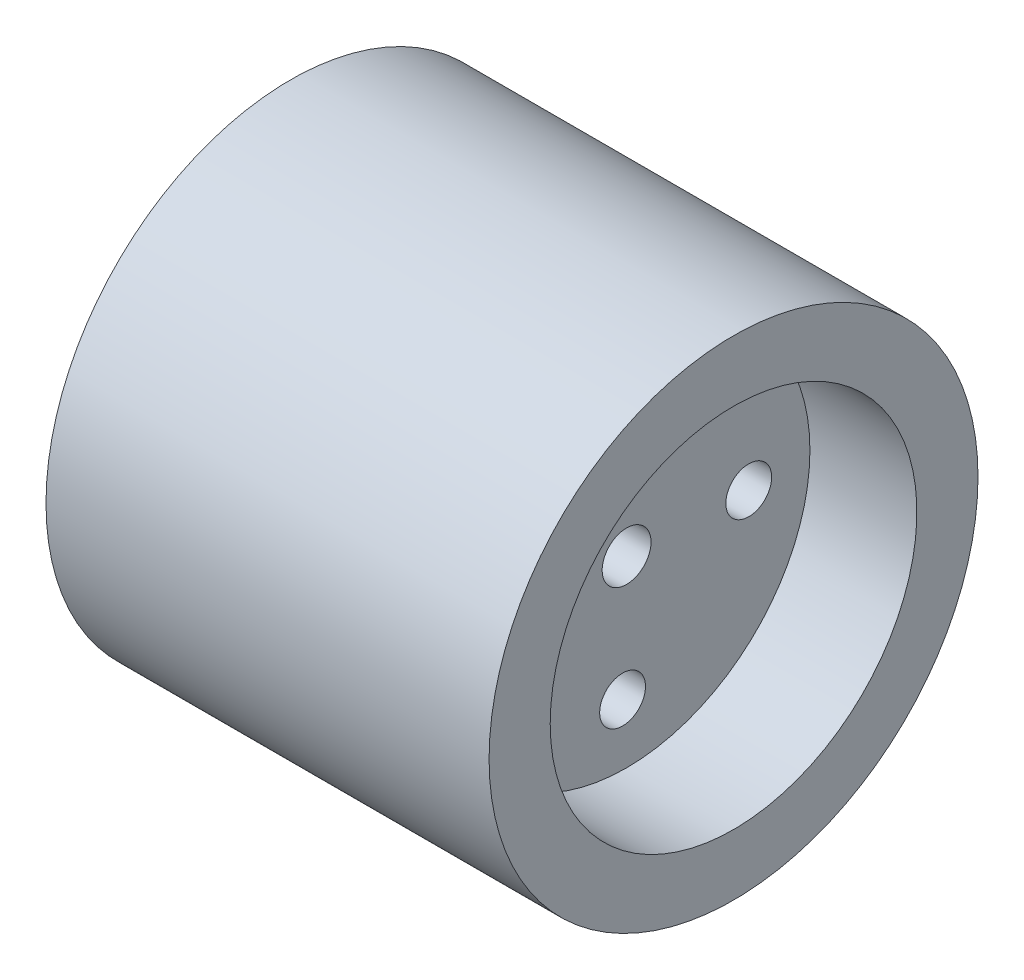
SolidWorks part; units mm, degrees
material "ABS"
ref_plane "Front Plane" through (0, 0, 0) normal (0, 0, 1) x (1, 0, 0)
ref_plane "Top Plane" through (0, 0, 0) normal (0, 1, 0) x (1, 0, 0)
ref_plane "Right Plane" through (0, 0, 0) normal (1, 0, 0) x (0, 0, -1)
sketch "Sketch3" plane through (0, 0, 0) normal (0, 0, 1) x (1, 0, 0)
  line L0 (0, 0) -> (18, 0) construction
  line L1 (-7, 1.6) -> (6, 1.6)
  line L2 (6, 1.6) -> (6, 12)
  line L6 (15, 12) -> (15, 16)
  line L7 (15, 16) -> (-14, 16)
  line L9 (-16, 13) -> (-7, 13)
  line L10 (-7, 13) -> (-7, 1.6)
  line L11 (15, 12) -> (6, 12)
  line L12 (-16, 18) -> (-16, 13)
  line L15 (-16, 18) -> (-14, 18)
  line L16 (-14, 16) -> (-14, 18)
  dimension "D1" = 3.2
  dimension "D2" = 9
  dimension "D3" = 32
  dimension "D4" = 31
  dimension "D5" = 13
  dimension "D6" = 18
  dimension "D7" = 24
  dimension "D8" = 3
  dimension "D9" = 3
  dimension "D10" = 2
  dimension "D11" = 2
revolve "Revolve1" add sketch "Sketch3" angle 360 about L0
sketch "Sketch4" plane through (-7, 0, 0) normal (-1, 0, 0) x (0, 0, 1)
  circle A0 centre (0.2626, -7.9957) radius 1.5
  circle A1 centre (-7.9957, -0.2626) radius 1.5
  circle A2 centre (-0.2626, 7.9957) radius 1.5
  circle A3 centre (7.9957, 0.2626) radius 1.5
extrude "Cut-Extrude1" cut sketch "Sketch4" against normal blind 17
sketch "Sketch5" plane through (6, 0, 0) normal (1, 0, 0) x (0, 0, -1)
  circle A0 centre (0, 0) radius 12
  circle A1 centre (7.9957, -0.2626) radius 1.5
  circle A2 centre (-0.2626, -7.9957) radius 1.5
  circle A3 centre (-7.9957, 0.2626) radius 1.5
  circle A4 centre (0.2626, 7.9957) radius 1.5
  circle A5 centre (0, 0) radius 1.6
extrude "Boss-Extrude1" add sketch "Sketch5" along normal blind 2
sketch "Sketch6" plane through (0, 0, 0) normal (0, 0, 1) x (1, 0, 0)
  line L0 (-16, -18) -> (-14, -18)
  line L1 (-14, -18) -> (-14, 18)
  line L2 (-14, 18) -> (-16, 18)
  line L3 (-16, 18) -> (-16, -18)
extrude "Cut-Extrude2" cut sketch "Sketch6" against normal through all both and the other way through all
